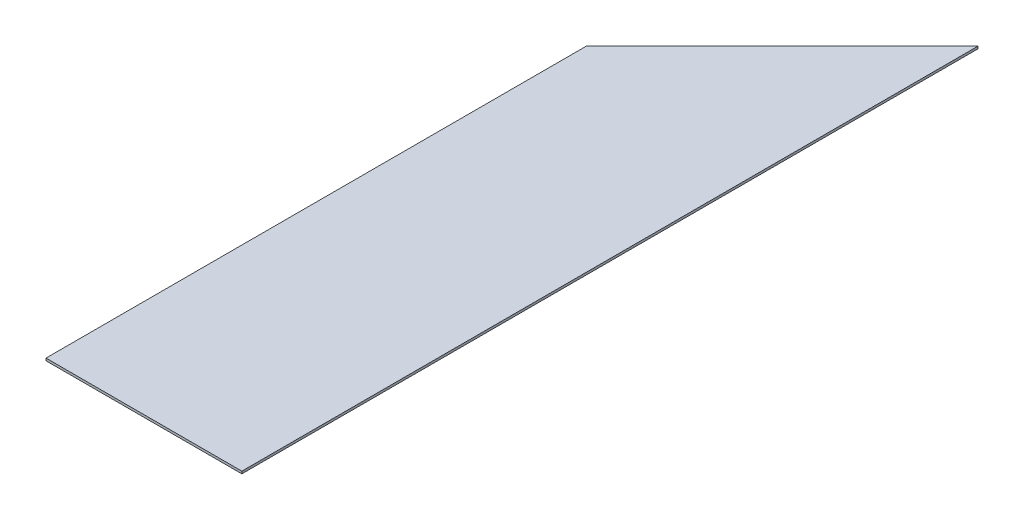
SolidWorks part; units mm, degrees
material "7075-O (SS)"
ref_plane "Front Plane" through (0, 0, 0) normal (0, 0, 1) x (1, 0, 0)
ref_plane "Top Plane" through (0, 0, 0) normal (0, 1, 0) x (1, 0, 0)
ref_plane "Right Plane" through (0, 0, 0) normal (1, 0, 0) x (0, 0, -1)
sketch "Sketch1" plane through (0, 0, 0) normal (0, 0, 1) x (1, 0, 0)
  line L0 (0, 0) -> (0, 8.5)
  line L1 (0, 8.5) -> (1, 8.5)
  line L2 (1, 8.5) -> (1, 13.5)
  line L3 (1, 13.5) -> (2, 13.5)
  line L4 (2, 13.5) -> (2, 2)
  line L5 (2, 2) -> (13.5, 2)
  line L6 (13.5, 2) -> (13.5, 1)
  line L7 (13.5, 1) -> (8.5, 1)
  line L8 (8.5, 1) -> (8.5, 0)
  line L9 (8.5, 0) -> (0, 0)
  line L10 (100, 0) -> (91.5, 0)
  line L11 (91.5, 0) -> (91.5, 1)
  line L12 (91.5, 1) -> (86.5, 1)
  line L13 (86.5, 1) -> (86.5, 2)
  line L14 (86.5, 2) -> (98, 2)
  line L15 (98, 2) -> (98, 13.5)
  line L16 (98, 13.5) -> (99, 13.5)
  line L17 (99, 13.5) -> (99, 8.5)
  line L18 (99, 8.5) -> (100, 8.5)
  line L19 (100, 8.5) -> (100, 0)
  dimension "D1" = 8.5
  dimension "D2" = 8.5
  dimension "D3" = 1
  dimension "D4" = 1
  dimension "D5" = 1
  dimension "D6" = 1
  dimension "D7" = 5
  dimension "D8" = 5
  dimension "D9" = 8.5
  dimension "D10" = 5
  dimension "D11" = 1
  dimension "D12" = 1
  dimension "D13" = 1
  dimension "D14" = 1
  dimension "D15" = 8.5
  dimension "D16" = 5
  dimension "D17" = 100
extrude "Boss-Extrude1" add sketch "Sketch1" along normal blind 327.5
sketch "Sketch2" plane through (0, 2, 0) normal (0, 1, 0) x (1, 0, 0)
  line L0 (86.5, 0) -> (13.5, -73)
  line L1 (13.5, -327.5) -> (13.5, 0) construction
  line L2 (13.5, -73) -> (13.5, -85.0208)
  line L3 (13.5, -85.0208) -> (86.5, -12.0208)
  line L4 (86.5, -327.5) -> (86.5, 0) construction
  line L5 (86.5, -12.0208) -> (86.5, 0)
  dimension "D1" = 8.5
  dimension "D2" = 45
extrude "Boss-Extrude2" add sketch "Sketch2" against normal blind 2
sketch "Sketch3" plane through (0, 1, 0) normal (0, -1, 0) x (1, 0, 0)
  line L0 (13.5, 85.0208) -> (8.5, 90.0208)
  line L1 (8.5, 327.5) -> (8.5, 0) construction
  line L2 (13.5, 73) -> (8.5, 78)
  line L3 (8.5, 78) -> (8.5, 90.0208)
  line L4 (13.5, 85.0208) -> (13.5, 73)
  line L5 (13.5, 85.0208) -> (86.5, 12.0208) construction
  line L6 (86.5, 0) -> (13.5, 73) construction
  line L7 (86.5, 12.0208) -> (91.5, 7.0208)
  line L8 (91.5, 327.5) -> (91.5, 0) construction
  line L9 (91.5, 7.0208) -> (91.5, 0)
  line L10 (91.5, 0) -> (86.5, 0)
  line L11 (86.5, 0) -> (86.5, 12.0208)
  line M5 (13.5, 73) -> (13.5, 85.0208)
  line M8 (8.5, 327.5) -> (8.5, 0)
  dimension "D1" = 180
  dimension "D2" = 180
  dimension "D3" = 180
extrude "Boss-Extrude4" add sketch "Sketch3" along normal blind 1 contours L2 L0 M5 M8 | L11 L10 L9 L7
sketch "Sketch4" plane through (0, 0, 0) normal (0, -1, 0) x (1, 0, 0)
  line L0 (0, 327.5) -> (0, 0) construction
  line L1 (100, 327.5) -> (0, 327.5)
  line L2 (100, 327.5) -> (100, 319)
  line L3 (100, 319) -> (0, 319)
  line L4 (0, 327.5) -> (0, 319)
  dimension "D1" = 8.5
extrude "Boss-Extrude5" add sketch "Sketch4" against normal blind 2
sketch "Sketch5" plane through (0, 2, 0) normal (0, 1, 0) x (1, 0, 0)
  line L0 (13.5, -65.9289) -> (79.4289, 0)
  line L1 (13.5, -73) -> (13.5, 0) construction
  line L2 (79.4289, 0) -> (86.5, 0)
  line L3 (86.5, 0) -> (13.5, -73)
  line L4 (13.5, -73) -> (13.5, -65.9289)
  dimension "D1" = 5
extrude "Boss-Extrude6" add sketch "Sketch5" against normal blind 1 separate body
sketch "Sketch7" plane through (0, 2, 0) normal (0, 1, 0) x (1, 0, 0)
  line L0 (98, -327.5) -> (98, 0) construction
  line L1 (2, -327.5) -> (98, -327.5)
  line L2 (2, -327.5) -> (2, -326.5)
  line L3 (2, -326.5) -> (98, -326.5)
  line L4 (98, -327.5) -> (98, -326.5)
  circle A0 centre (26.5, -326.5) radius 5
  circle A1 centre (73.5, -326.5) radius 5
  dimension "D2" = 10
  dimension "D3" = 10
  dimension "D1" = 1
  dimension "D4" = 25.5
  dimension "D5" = 25.5
extrude "Cut-Extrude2" cut sketch "Sketch7" against normal blind 1 contours L3 A1 | A0
mirror "Mirror1" about plane through (1, 13.5, 327.5) normal (0, -1, 0) of bodies 107 110
sketch "Sketch8" plane through (0, 0, 0) normal (0, 0, -1) x (-1, 0, 0)
  line L1 (-100, 0) -> (0, 0)
  line L2 (-100, 0) -> (-100, 13.5)
  line L3 (-100, 13.5) -> (0, 13.5)
  line L4 (0, 0) -> (0, 13.5)
  dimension "D1" = 13.5
extrude "Cut-Extrude3" cut sketch "Sketch8" against normal blind 400
sketch "Sketch9" plane through (0, 0, 0) normal (0, 0, -1) x (-1, 0, 0)
  line L1 (-1, 18.5) -> (-2, 18.5)
  line L2 (-1, 18.5) -> (-1, 13.5)
  line L3 (-1, 13.5) -> (-2, 13.5)
  line L4 (-2, 18.5) -> (-2, 13.5)
extrude "Cut-Extrude4" cut sketch "Sketch9" against normal blind 84.5
sketch "Sketch10" plane through (0, 27, 0) normal (0, 1, 0) x (1, 0, 0)
  line L0 (8.5, -90.0208) -> (91.5, -7.0208) construction
  line L3 (8.5, -319) -> (8.5, -90.0208) construction
  line L4 (8.5, -90.0208) -> (91.5, -7.0208)
  line L5 (91.5, -319) -> (8.5, -319)
  line L6 (91.5, -319) -> (91.5, -90.0208)
  line L7 (91.5, -90.0208) -> (8.5, -90.0208)
  line L8 (8.5, -319) -> (8.5, -90.0208)
  line L9 (91.5, -7.0208) -> (91.5, -90.0208)
  line M1 (8.5, -319) -> (8.5, -90.0208)
  line M2 (8.5, -90.0208) -> (91.5, -7.0208)
  line M3 (91.5, -7.0208) -> (91.5, -319)
  line M4 (91.5, -319) -> (8.5, -319)
extrude "Boss-Extrude7" add sketch "Sketch10" along normal blind 1 separate body contours L7 M3 M2 | L7 M3 M1 M4
sketch "Sketch12" plane through (0, 0, 327.5) normal (0, 0, 1) x (1, 0, 0)
  line L1 (0, 27) -> (120.6198, 27)
  line L2 (0, 27) -> (0, 7.1565)
  line L3 (0, 7.1565) -> (120.6198, 7.1565)
  line L4 (120.6198, 27) -> (120.6198, 7.1565)
extrude "Cut-Extrude6" cut sketch "Sketch12" against normal blind 400 contours L3 L4 L1 L2
